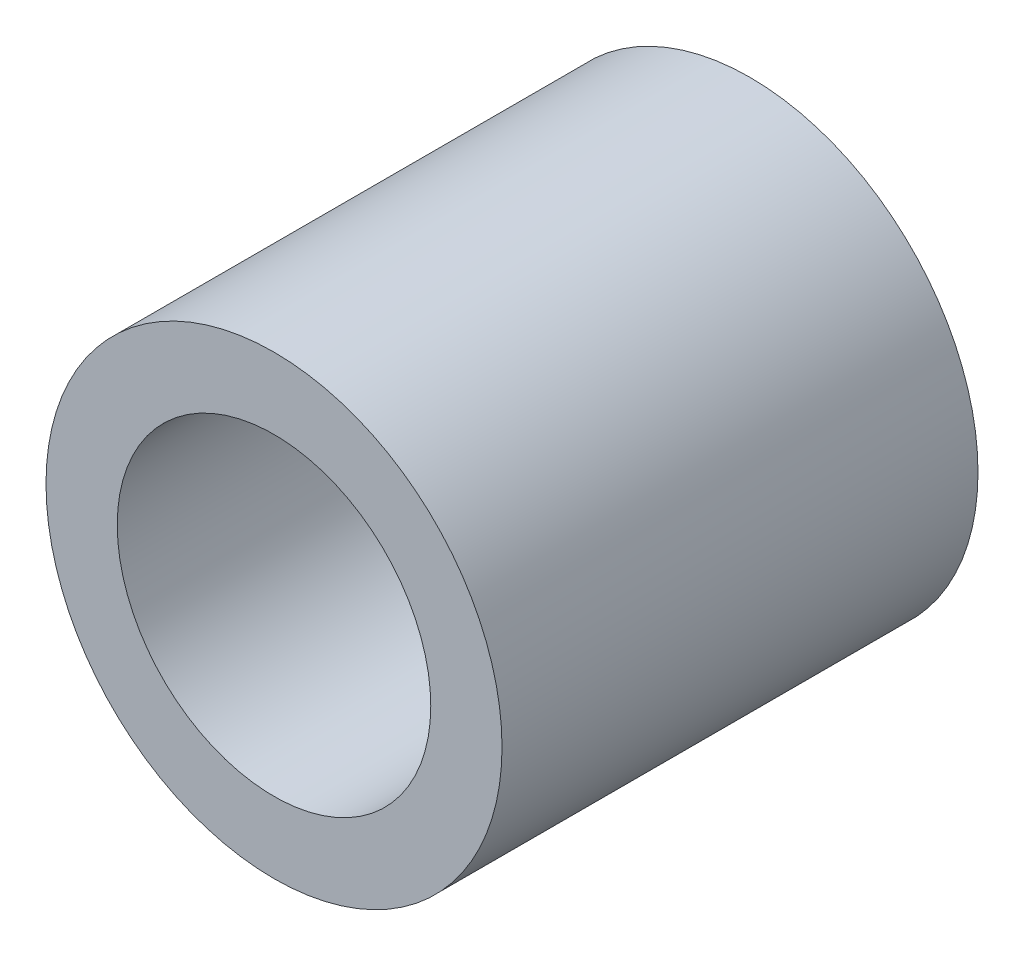
SolidWorks part; units mm, degrees
ref_plane "Front Plane" through (0, 0, 0) normal (0, 0, 1) x (1, 0, 0)
ref_plane "Top Plane" through (0, 0, 0) normal (0, 1, 0) x (1, 0, 0)
ref_plane "Right Plane" through (0, 0, 0) normal (1, 0, 0) x (0, 0, -1)
sketch "Sketch1" plane through (0, 0, 0) normal (0, 0, 1) x (1, 0, 0)
  circle A0 centre (0, 0) radius 2.75
  circle A1 centre (0, 0) radius 4
  dimension "D1" = 5.5
  dimension "D2" = 8
extrude "Boss-Extrude1" add sketch "Sketch1" against normal blind 8.35
